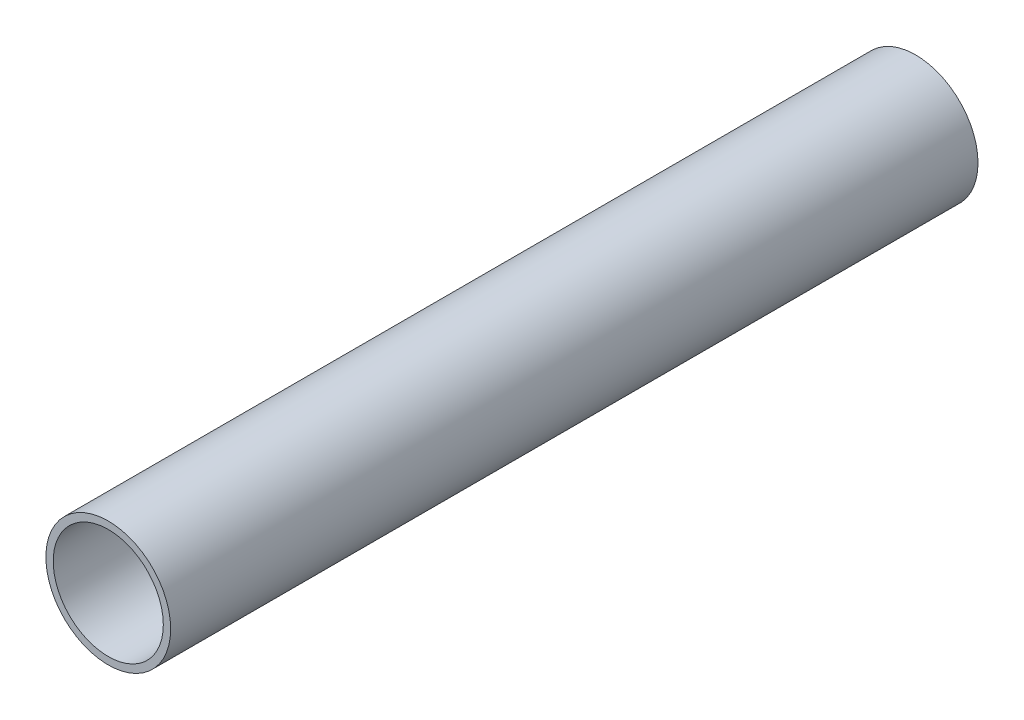
SolidWorks part; units mm, degrees
ref_plane "Front Plane" through (0, 0, 0) normal (0, 0, 1) x (1, 0, 0)
ref_plane "Top Plane" through (0, 0, 0) normal (0, 1, 0) x (1, 0, 0)
ref_plane "Right Plane" through (0, 0, 0) normal (1, 0, 0) x (0, 0, -1)
sketch "Sketch1" plane through (0, 0, 0) normal (0, 0, 1) x (1, 0, 0)
  circle A0 centre (0, 0) radius 15
  circle A1 centre (0, 0) radius 17
  dimension "D1" = 30
  dimension "D2" = 2
extrude "Boss-Extrude1" add sketch "Sketch1" along normal mid plane 220 contours A1 A0
